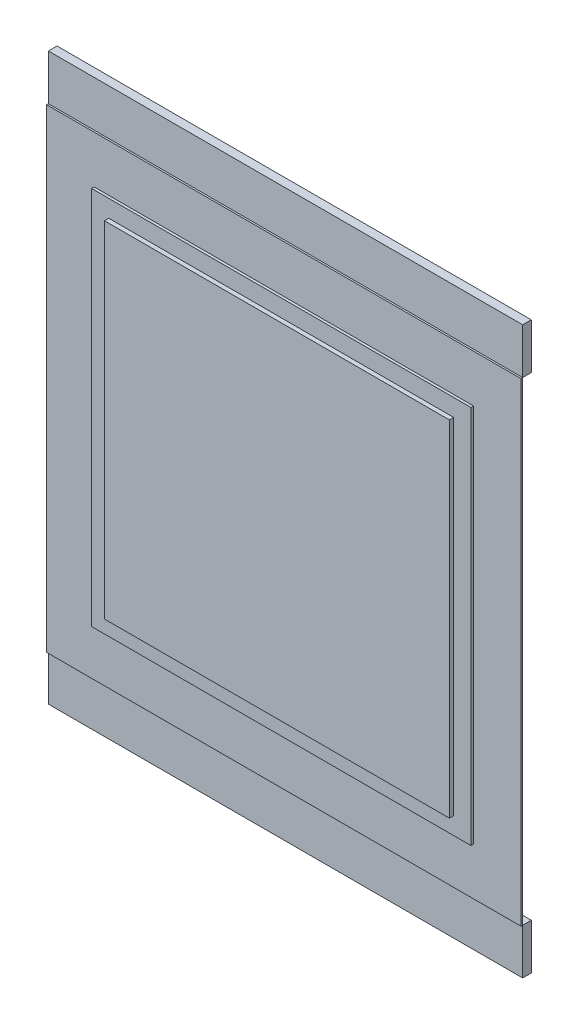
SolidWorks part; units mm, degrees
ref_plane "Front Plane" through (0, 0, 0) normal (1, 0, 0) x (0, 1, 0)
ref_plane "Top Plane" through (0, 0, 0) normal (0, 0, 1) x (0, 1, 0)
ref_plane "Right Plane" through (0, 0, 0) normal (0, 1, 0) x (-1, 0, 0)
sketch "Sketch1" plane through (0, 0, 0) normal (0, 0, 1) x (0, 1, 0)
  line L0 (-220, 220) -> (-220, -220)
  line L1 (200, 200) -> (-200, 200)
  line L2 (200, 200) -> (200, -200)
  line L3 (200, -200) -> (-200, -200)
  line L4 (-200, 200) -> (-200, -200)
  line L5 (200, 200) -> (-200, -200) construction
  line L6 (200, -200) -> (-200, 200) construction
  line L7 (220, -220) -> (-220, -220)
  line L8 (220, 220) -> (220, -220)
  line L9 (220, 220) -> (-220, 220)
  line L10 (-275, 275) -> (-275, -275)
  line L11 (275, -275) -> (-275, -275)
  line L12 (275, 275) -> (275, -275)
  line L13 (275, 275) -> (-275, 275)
  line L14 (0, -302.5) -> (0, 302.5) construction
  line L15 (275, 275) -> (328, 275)
  line L16 (275, 275) -> (275, -275)
  line L17 (275, -275) -> (328, -275)
  line L18 (328, 275) -> (328, -275)
  line L19 (-275, -275) -> (-328, -275)
  line L20 (-328, 275) -> (-328, -275)
  line L21 (-275, 275) -> (-328, 275)
  line L22 (-275, 275) -> (-275, -275)
  line L23 (301.5, 275) -> (301.5, -275) construction
  line L24 (-301.5, -275) -> (-301.5, 275) construction
  point P0 (0, 0)
  dimension "D3" = 400
  dimension "D4" = 53
  dimension "D5" = 550
  dimension "D1" = 20
  dimension "D2" = 55
extrude "Boss-Extrude1" add sketch "Sketch1" along normal blind 10 contours L1 L4 L3 L2
sketch "Sketch2" plane through (0, 0, 0) normal (0, 0, -1) x (1, 0, 0)
  line L1 (-220, 220) -> (220, 220)
  line L2 (-220, 220) -> (-220, -220)
  line L3 (-220, -220) -> (220, -220)
  line L4 (220, 220) -> (220, -220)
extrude "Boss-Extrude2" add sketch "Sketch2" against normal blind 5
sketch "Sketch3" plane through (0, 0, 0) normal (0, 0, -1) x (1, 0, 0)
  line L1 (-275, 275) -> (275, 275)
  line L2 (-275, 275) -> (-275, -275)
  line L3 (-275, -275) -> (275, -275)
  line L4 (275, 275) -> (275, -275)
extrude "Boss-Extrude3" add sketch "Sketch3" against normal blind 2
sketch "Sketch4" plane through (0, 0, 0) normal (0, 0, -1) x (1, 0, 0)
  line L1 (-275, 275) -> (275, 275)
  line L2 (-275, 275) -> (-275, 328)
  line L3 (-275, 328) -> (275, 328)
  line L4 (275, 275) -> (275, 328)
  line L5 (-275, -275) -> (275, -275)
  line L6 (-275, -275) -> (-275, -328)
  line L7 (-275, -328) -> (275, -328)
  line L8 (275, -275) -> (275, -328)
extrude "Boss-Extrude4" add sketch "Sketch4" along normal blind 10 separate body
